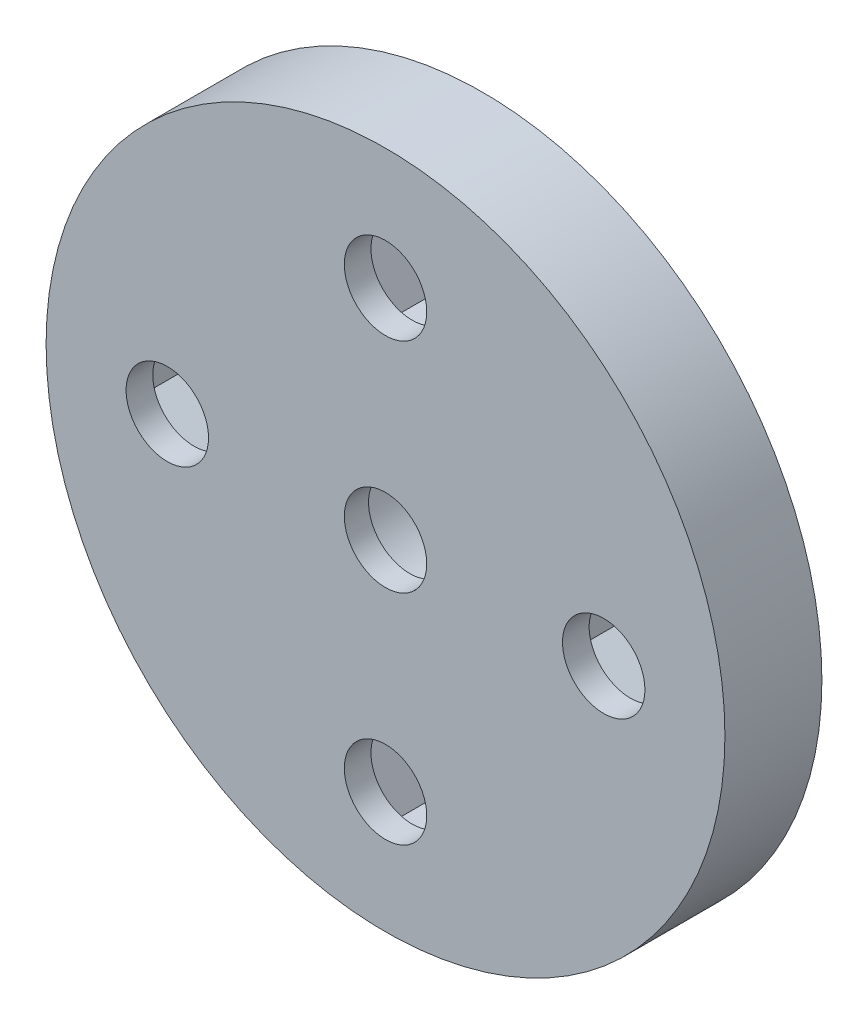
SolidWorks part; units mm, degrees
ref_plane "Front Plane" through (0, 0, 0) normal (0, 0, 1) x (1, 0, 0)
ref_plane "Top Plane" through (0, 0, 0) normal (0, 1, 0) x (1, 0, 0)
ref_plane "Right Plane" through (0, 0, 0) normal (1, 0, 0) x (0, 0, -1)
sketch "Hub_disc_OD28_thickness4_profile" plane through (0, 0, 0) normal (0, 0, 1) x (1, 0, 0)
  circle A0 centre (0, 0) radius 14
  dimension "D1" = 28
extrude "Hub_disc_OD28_thickness4" add sketch "Hub_disc_OD28_thickness4_profile" along normal blind 4
sketch "MG996R_spline_press_socket_D5p80_depth3_profile" plane through (0, 0, 0) normal (0, 0, 1) x (1, 0, 0)
  circle A0 centre (0, 0) radius 2.9
  dimension "D1" = 5.8
extrude "MG996R_spline_press_socket_D5p80_depth3" cut sketch "MG996R_spline_press_socket_D5p80_depth3_profile" along normal blind 3
sketch "M3_centre_screw_clearance_through_floor_profile" plane through (0, 0, 0) normal (0, 0, 1) x (1, 0, 0)
  circle A0 centre (0, 0) radius 1.7
  dimension "D1" = 3.4
extrude "M3_centre_screw_clearance_through_floor" cut sketch "M3_centre_screw_clearance_through_floor_profile" along normal through all from offset 50
sketch "Link_M3_clearance_PCD18_profile" plane through (0, 0, 0) normal (0, 0, 1) x (1, 0, 0)
  circle A0 centre (9, 0) radius 1.7
  circle A1 centre (0, 9) radius 1.7
  circle A2 centre (-9, 0) radius 1.7
  circle A3 centre (0, -9) radius 1.7
  dimension "D1" = 3.4
  dimension "D2" = 3.4
  dimension "D3" = 3.4
  dimension "D4" = 3.4
extrude "Link_M3_clearance_PCD18" cut sketch "Link_M3_clearance_PCD18_profile" along normal through all from offset 50
sketch "Captured_M3_nut_pockets_AF5p7_profile" plane through (0, 0, 0) normal (0, 0, 1) x (1, 0, 0)
  line L0 (11.85, 1.6454) -> (9, 3.2909)
  line L1 (9, 3.2909) -> (6.15, 1.6454)
  line L2 (6.15, 1.6454) -> (6.15, -1.6454)
  line L3 (6.15, -1.6454) -> (9, -3.2909)
  line L4 (9, -3.2909) -> (11.85, -1.6454)
  line L5 (11.85, -1.6454) -> (11.85, 1.6454)
  line L6 (-1.6454, 11.85) -> (-3.2909, 9)
  line L7 (-3.2909, 9) -> (-1.6454, 6.15)
  line L8 (-1.6454, 6.15) -> (1.6454, 6.15)
  line L9 (1.6454, 6.15) -> (3.2909, 9)
  line L10 (3.2909, 9) -> (1.6454, 11.85)
  line L11 (1.6454, 11.85) -> (-1.6454, 11.85)
  line L12 (-11.85, -1.6454) -> (-9, -3.2909)
  line L13 (-9, -3.2909) -> (-6.15, -1.6454)
  line L14 (-6.15, -1.6454) -> (-6.15, 1.6454)
  line L15 (-6.15, 1.6454) -> (-9, 3.2909)
  line L16 (-9, 3.2909) -> (-11.85, 1.6454)
  line L17 (-11.85, 1.6454) -> (-11.85, -1.6454)
  line L18 (1.6454, -11.85) -> (3.2909, -9)
  line L19 (3.2909, -9) -> (1.6454, -6.15)
  line L20 (1.6454, -6.15) -> (-1.6454, -6.15)
  line L21 (-1.6454, -6.15) -> (-3.2909, -9)
  line L22 (-3.2909, -9) -> (-1.6454, -11.85)
  line L23 (-1.6454, -11.85) -> (1.6454, -11.85)
extrude "Captured_M3_nut_pockets_depth2p9" cut sketch "Captured_M3_nut_pockets_AF5p7_profile" along normal blind 2.9
